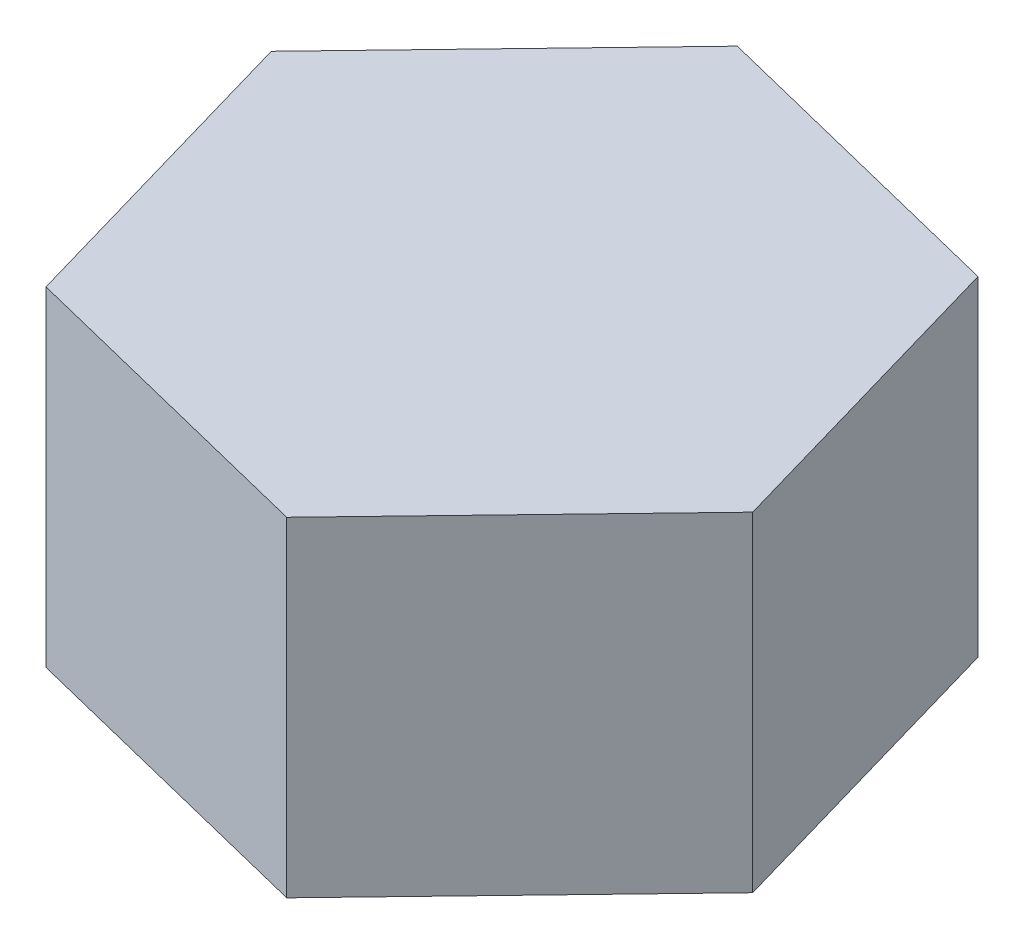
SolidWorks part; units mm, degrees
ref_plane "前视基准面" through (0, 0, 0) normal (0, 0, 1) x (1, 0, 0)
ref_plane "上视基准面" through (0, 0, 0) normal (0, 1, 0) x (1, 0, 0)
ref_plane "右视基准面" through (0, 0, 0) normal (1, 0, 0) x (0, 0, -1)
sketch "草图1" plane through (0, 0, 0) normal (0, 1, 0) x (1, 0, 0)
  line L1 (13.8687, 14.4104) -> (-5.5454, 19.2158)
  line L2 (-5.5454, 19.2158) -> (-19.4141, 4.8054)
  line L3 (-19.4141, 4.8054) -> (-13.8687, -14.4104)
  line L4 (-13.8687, -14.4104) -> (5.5454, -19.2158)
  line L5 (5.5454, -19.2158) -> (19.4141, -4.8054)
  line L6 (19.4141, -4.8054) -> (13.8687, 14.4104)
  circle A0 centre (0, 0) radius 17.3205 construction
  dimension "D1" = 40
extrude "凸台-拉伸1" add sketch "草图1" along normal blind 20
